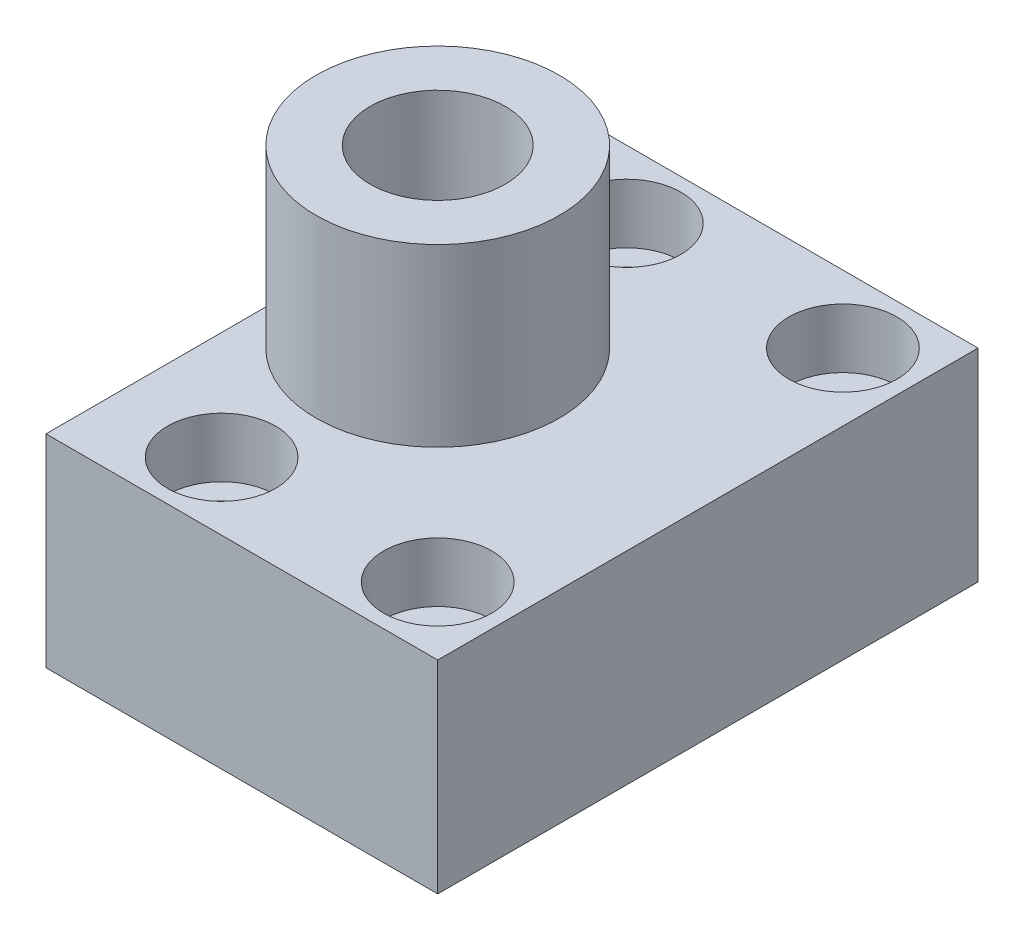
SolidWorks part; units mm, degrees
material "Д16Т ГОСТ 4784-74"
ref_plane "Спереди" through (0, 0, 0) normal (0, 0, 1) x (1, 0, 0)
ref_plane "Сверху" through (0, 0, 0) normal (0, 1, 0) x (1, 0, 0)
ref_plane "Справа" through (0, 0, 0) normal (1, 0, 0) x (0, 0, -1)
sketch "Эскиз1" plane through (0, 0, 0) normal (0, 0, 1) x (1, 0, 0)
  line L2 (7.5, 0) -> (7.5, -11)
  line L3 (7.5, -11) -> (15, -11)
  line L4 (15, -11) -> (15, -26)
  line L5 (15, -26) -> (-14, -26)
  line L6 (0, 0) -> (0, -27) construction
  line L10 (0, 2) -> (7.5, 2)
  line L11 (7.5, 2) -> (7.5, 0)
  line L15 (0, 2) -> (-14, 2)
  line L17 (-14, -26) -> (-14, 2)
  dimension "D1" = 14
  dimension "D2" = 2
  dimension "D3" = 15
  dimension "D4" = 26
  dimension "D5" = 15
  dimension "D6" = 15
extrude "Бобышка-Вытянуть1" add sketch "Эскиз1" along normal blind 40
sketch "Эскиз9" plane through (0, 2, 0) normal (0, 1, 0) x (1, 0, 0)
  line L0 (-5, -20) -> (7.5, -20) construction
  line L1 (7.5, -40) -> (7.5, 0) construction
  circle A0 centre (-5, -20) radius 5
  dimension "D1" = 10
  dimension "D2" = 5
extrude "Вырез-Вытянуть3" cut sketch "Эскиз9" against normal through all
sketch "Эскиз16" plane through (0, 2, 0) normal (0, 1, 0) x (1, 0, 0)
  circle A0 centre (-5, -20) radius 9
  dimension "D1" = 18
extrude "Вырез-Вытянуть4" cut sketch "Эскиз16" against normal up to surface (13 mm away) flip side to cut up to face at (11.25, -11, 20)
hole_wizard "Цековка для  винта с внутренним шестигранником M41" positions "Эскиз18" profile "Эскиз17" counterbore size "M4" standard "DIN" end condition through all
sketch "Эскиз18" plane through (0, -11, 0) normal (0, 1, 0) x (-1, 0, 0)
  line L0 (14, 40) -> (14, 20) construction
  line L1 (-15, 40) -> (14, 40) construction
  line L2 (-15, 0) -> (14, 0) construction
  line L4 (-15, 40) -> (-15, 0) construction
  point P0 (-10, 35)
  point P1 (-10, 5)
  point P3 (6, 35)
  point P5 (6, 5)
  dimension "D1" = 8
  dimension "D2" = 5
  dimension "D3" = 5
  dimension "D4" = 5
sketch "Эскиз17" plane through (10, -11, 35) normal (1, 0, 0) x (0, 0, 1)
  line L0 (0, 0) -> (0, 15)
  line L1 (0, 15) -> (2.25, 15)
  line L3 (2.25, 15) -> (2.25, 4.4)
  line L4 (2.25, 4.4) -> (4, 4.4)
  line L5 (4, 4.4) -> (4, 0)
  line L7 (4, 0) -> (0, 0)
  line L11 (0, -6.35) -> (0, 107.95) construction
  dimension "Диаметр сквозного отверстия" = 4.5
  dimension "Глубина сквозного отверстия" = 15
  dimension "Диаметр цековки" = 8
  dimension "Глубина цековки" = 4.4
sketch "Эскиз19" plane through (0, -26, 0) normal (0, -1, 0) x (1, 0, 0)
  circle A0 centre (-5, 20) radius 8
  dimension "D1" = 16
extrude "Вырез-Вытянуть5" cut sketch "Эскиз19" against normal blind 5
